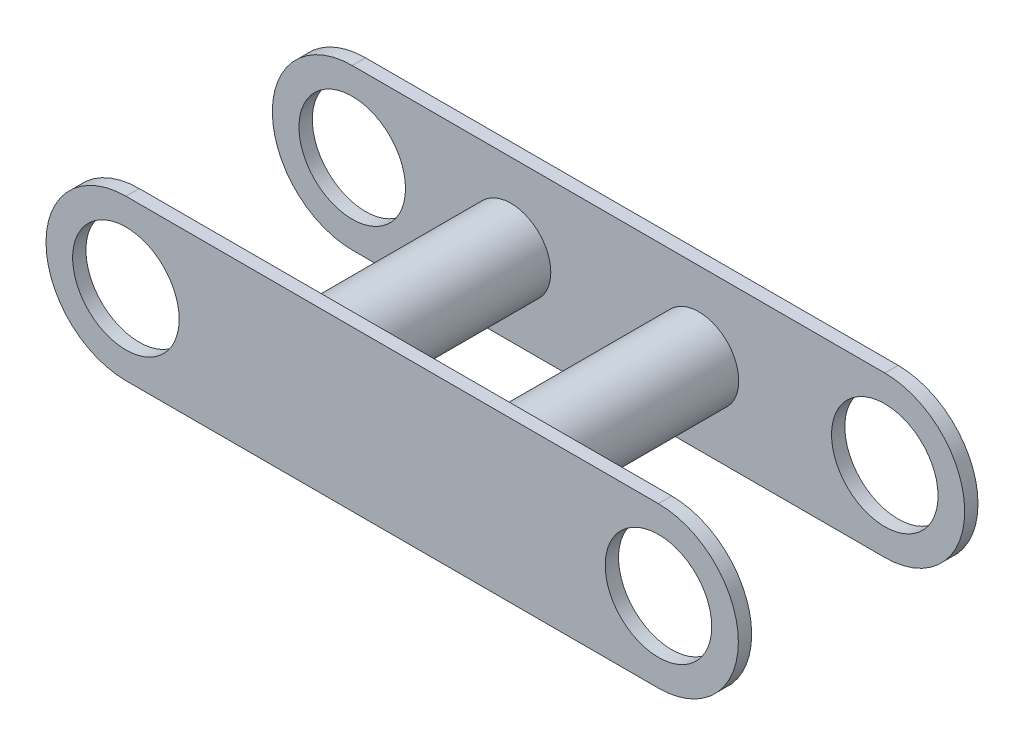
SolidWorks part; units mm, degrees
ref_plane "前视基准面" through (0, 0, 0) normal (0, 0, 1) x (1, 0, 0)
ref_plane "上视基准面" through (0, 0, 0) normal (0, 1, 0) x (1, 0, 0)
ref_plane "右视基准面" through (0, 0, 0) normal (1, 0, 0) x (0, 0, -1)
sketch "草图1" plane through (0, 0, 0) normal (0, 0, 1) x (1, 0, 0)
  line L0 (-21.5943, 0) -> (178.4057, 0) construction
  line L1 (-21.5943, 30) -> (178.4057, 30)
  line L2 (-21.5943, -30) -> (178.4057, -30)
  arc A0 (-21.5943, 30) -> (-21.5943, -30) centre (-21.5943, 0) ccw
  arc A1 (178.4057, -30) -> (178.4057, 30) centre (178.4057, 0) ccw
  circle A2 centre (178.4057, 0) radius 20
  circle A3 centre (-21.5943, 0) radius 20
  point P3 (78.4057, 0)
  dimension "D2" = 60
  dimension "D3" = 30
  dimension "D4" = 40
  dimension "D1" = 200
extrude "凸台-拉伸3" add sketch "草图1" along normal blind 5
sketch "草图5" plane through (0, 0, 5) normal (0, 0, 1) x (1, 0, 0)
  circle A0 centre (37.9719, 0) radius 15
  circle A1 centre (108.5504, 0) radius 15
  dimension "D1" = 30
extrude "凸台-拉伸4" add sketch "草图5" along normal blind 80
pattern_linear "阵列(线性)2" count 2 spacing 85 along (0, 0, 1) of "凸台-拉伸3"
